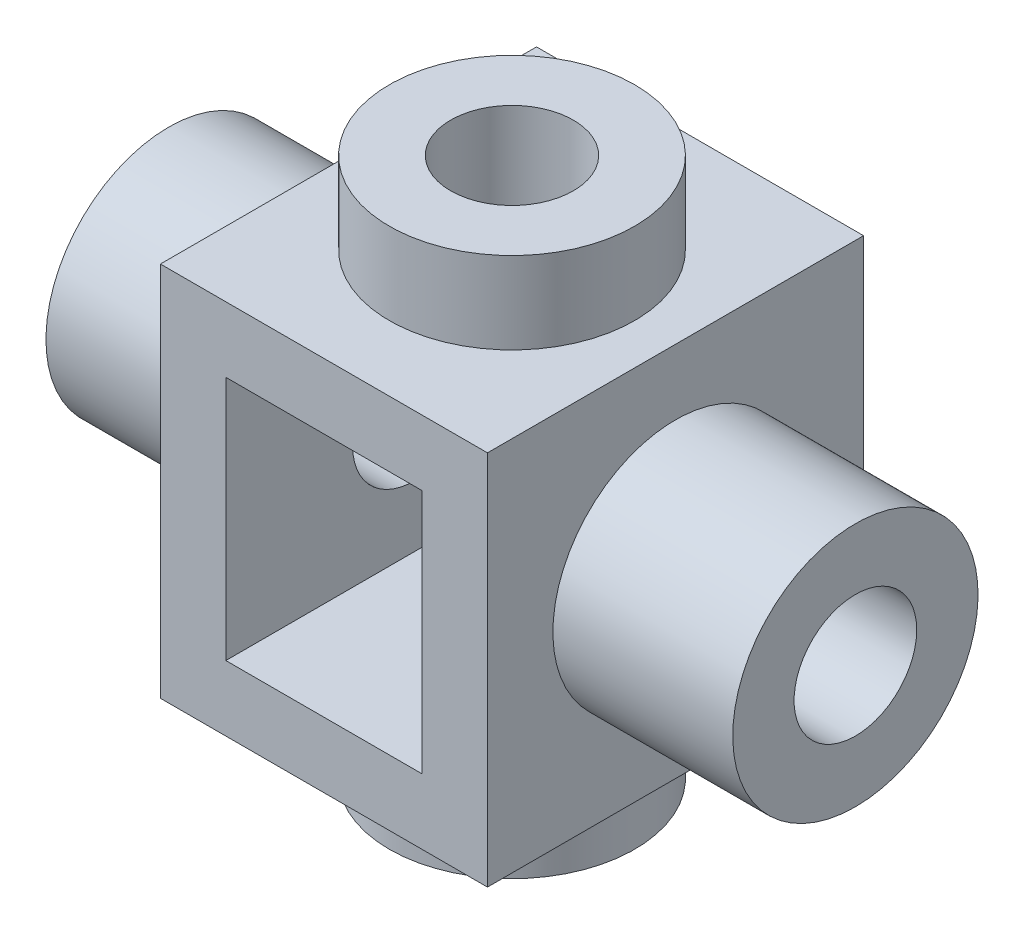
SolidWorks part; units mm, degrees
ref_plane "Front Plane" through (0, 0, 0) normal (0, 0, 1) x (1, 0, 0)
ref_plane "Top Plane" through (0, 0, 0) normal (0, 1, 0) x (1, 0, 0)
ref_plane "Right Plane" through (0, 0, 0) normal (1, 0, 0) x (0, 0, -1)
ref_plane "Plane1" through (-20, 0, 0) normal (-1, 0, 0) x (0, -1, 0)
sketch "Sketch1" plane through (-20, 0, 0) normal (-1, 0, 0) x (0, -1, 0)
  line L0 (23, 0) -> (-23, 0)
  line L1 (-23, 0) -> (-23, -46)
  line L2 (-23, -46) -> (23, -46)
  line L3 (23, -46) -> (23, 0)
  dimension "D1" = 23
  dimension "D2" = 23
extrude "Boss-Extrude1" add sketch "Sketch1" against normal blind 40
sketch "Sketch2" plane through (0, 0, -46) normal (0, 0, -1) x (-1, 0, 0)
  line L0 (12, -15) -> (12, 15)
  line L1 (12, 15) -> (-12, 15)
  line L2 (-12, 15) -> (-12, -15)
  line L3 (-12, -15) -> (12, -15)
  line L4 (20, 23) -> (20, -23) construction
  line L5 (-20, 23) -> (20, 23) construction
  dimension "D1" = 8
  dimension "D2" = 32
  dimension "D3" = 8
  dimension "D4" = 38
extrude "Cut-Extrude1" cut sketch "Sketch2" against normal through all
ref_plane "Plane2" through (0, 0, -23) normal (0, 0, -1) x (-1, 0, 0)
sketch "Sketch3" plane through (0, 0, -23) normal (0, 0, -1) x (-1, 0, 0)
  line L0 (-15, -33) -> (0, -33)
  line L1 (0, -33) -> (0, -23)
  line L2 (0, -23) -> (-15, -23)
  line L3 (-15, -23) -> (-15, -33)
  line L4 (0, -33) -> (0, -23) construction
  dimension "D1" = 15
  dimension "D2" = 23
  dimension "D3" = 33
revolve "Revolve1" add sketch "Sketch3" angle 360 about L4
ref_plane "Plane3" through (0, 0, -23) normal (0, 0, 1) x (1, 0, 0)
sketch "Sketch4" plane through (0, 0, -23) normal (0, 0, 1) x (1, 0, 0)
  line L0 (15, 33) -> (0, 33)
  line L1 (0, 33) -> (0, 23)
  line L2 (0, 23) -> (15, 23)
  line L3 (15, 23) -> (15, 33)
  line L4 (0, 33) -> (0, 23) construction
  dimension "D1" = 15
  dimension "D2" = 23
  dimension "D3" = 33
revolve "Revolve2" add sketch "Sketch4" angle 360 about L4
sketch "Sketch5" plane through (0, 0, -23) normal (0, 0, 1) x (1, 0, 0)
  line L0 (-42, 15) -> (-42, 0)
  line L1 (-42, 0) -> (-20, 0)
  line L2 (-20, 0) -> (-20, 15)
  line L3 (-20, 15) -> (-42, 15)
  line L4 (-42, 0) -> (-20, 0) construction
  dimension "D1" = 20
  dimension "D2" = 42
  dimension "D3" = 15
revolve "Revolve3" add sketch "Sketch5" angle 360 about L4
sketch "Sketch6" plane through (0, 0, -23) normal (0, 0, -1) x (-1, 0, 0)
  line L0 (-42, 15) -> (-42, 0)
  line L1 (-42, 0) -> (-20, 0)
  line L2 (-20, 0) -> (-20, 15)
  line L3 (-20, 15) -> (-42, 15)
  line L4 (-42, 0) -> (-20, 0) construction
  dimension "D1" = 20
  dimension "D2" = 42
  dimension "D3" = 15
revolve "Revolve4" add sketch "Sketch6" angle 360 about L4
hole_wizard "Ø15.0 (15) Diameter Hole1" positions "Sketch8" profile "Sketch7" hole size "Ø15.0" standard "ANSI Metric"
sketch "Sketch8" plane through (0, -33, 0) normal (0, -1, 0) x (-1, 0, 0)
  circle A0 centre (0, 23) radius 15 construction
  point P0 (0, 23)
sketch "Sketch7" plane through (0, -33, -23) normal (1, 0, 0) x (0, 0, -1)
  line L0 (0, 0) -> (0, 18)
  line L1 (0, 18) -> (7.5, 18)
  line L2 (7.5, 18) -> (7.5, 0)
  line L5 (7.5, 0) -> (0, 0)
  line L11 (0, -6.35) -> (0, 107.95) construction
  dimension "Thru Hole Dia." = 15
  dimension "Thru Hole Depth" = 18
hole_wizard "Ø15.0 (15) Diameter Hole2" positions "Sketch10" profile "Sketch9" hole size "Ø15.0" standard "ANSI Metric"
sketch "Sketch10" plane through (0, 33, 0) normal (0, 1, 0) x (1, 0, 0)
  point P0 (0, 23)
  point P1 (0, 0)
sketch "Sketch9" plane through (0, 33, -23) normal (1, 0, 0) x (0, 0, 1)
  line L0 (0, 0) -> (0, 66)
  line L1 (0, 66) -> (7.5, 66)
  line L2 (7.5, 66) -> (7.5, 0)
  line L5 (7.5, 0) -> (0, 0)
  line L11 (0, -6.35) -> (0, 107.95) construction
  dimension "Thru Hole Dia." = 15
  dimension "Thru Hole Depth" = 66
hole_wizard "Ø15.0 (15) Diameter Hole3" positions "Sketch12" profile "Sketch11" hole size "Ø15.0" standard "ANSI Metric"
sketch "Sketch12" plane through (-42, 0, 0) normal (-1, 0, 0) x (0, 0, 1)
  point P0 (-23, 0)
  point P1 (0, 0)
sketch "Sketch11" plane through (-42, 0, -23) normal (0, 1, 0) x (0, 0, 1)
  line L0 (0, 0) -> (0, 30)
  line L1 (0, 30) -> (7.5, 30)
  line L2 (7.5, 30) -> (7.5, 0)
  line L5 (7.5, 0) -> (0, 0)
  line L11 (0, -6.35) -> (0, 107.95) construction
  dimension "Thru Hole Dia." = 15
  dimension "Thru Hole Depth" = 30
hole_wizard "Ø15.0 (15) Diameter Hole4" positions "Sketch14" profile "Sketch13" hole size "Ø15.0" standard "ANSI Metric"
sketch "Sketch14" plane through (42, 0, 0) normal (1, 0, 0) x (0, 0, -1)
  point P0 (23, 0)
sketch "Sketch13" plane through (42, 0, -23) normal (0, 1, 0) x (0, 0, -1)
  line L0 (0, 0) -> (0, 84)
  line L1 (0, 84) -> (7.5, 84)
  line L2 (7.5, 84) -> (7.5, 0)
  line L5 (7.5, 0) -> (0, 0)
  line L11 (0, -6.35) -> (0, 107.95) construction
  dimension "Thru Hole Dia." = 15
  dimension "Thru Hole Depth" = 84
